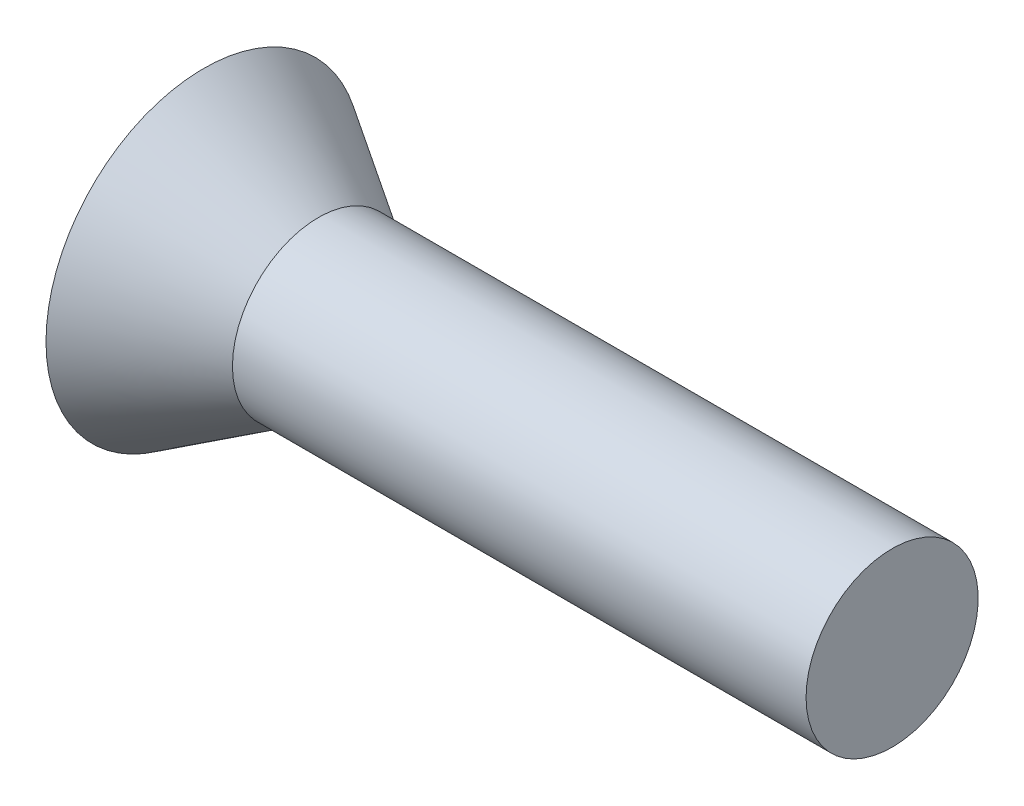
SolidWorks part; units mm, degrees
ref_plane "前视基准面" through (0, 0, 0) normal (0, 0, 1) x (1, 0, 0)
ref_plane "上视基准面" through (0, 0, 0) normal (0, 1, 0) x (1, 0, 0)
ref_plane "右视基准面" through (0, 0, 0) normal (1, 0, 0) x (0, 0, -1)
sketch "草图4" plane through (0, 0, 0) normal (0, 1, 0) x (1, 0, 0)
  line L0 (-2.1035, 0) -> (3.1765, 0) construction
  line L1 (0, 0) -> (0, 2.75)
  line L2 (0, 2.75) -> (2, 1.5)
  line L3 (2, 1.5) -> (12, 1.5)
  line L4 (12, 1.5) -> (12, 0)
  line L5 (12, 0) -> (0, 0)
  dimension "D1" = 2
  dimension "D2" = 2.75
  dimension "D3" = 1.5
  dimension "D4" = 10
revolve "旋转1" add sketch "草图4" angle 360 about L0
sketch "草图5" plane through (0, 0, 0) normal (-1, 0, 0) x (0, 0, 1)
  line L0 (-0.25, 0.25) -> (-1.25, 0.25)
  line L1 (1.25, -0.25) -> (0.25, -0.25)
  line L2 (1.25, -0.25) -> (1.25, 0.25)
  line L3 (1.25, 0.25) -> (0.25, 0.25)
  line L4 (-1.25, -0.25) -> (-1.25, 0.25)
  line L7 (0.25, -1.25) -> (-0.25, -1.25)
  line L8 (0.25, -1.25) -> (0.25, -0.25)
  line L9 (0.25, 1.25) -> (-0.25, 1.25)
  line L10 (-0.25, -1.25) -> (-0.25, -0.25)
  line L13 (-0.25, 0.25) -> (-0.25, 1.25)
  line L15 (0.25, 0.25) -> (0.25, 1.25)
  line L16 (-0.25, -0.25) -> (-1.25, -0.25)
  point P0 (0, 0)
  point P6 (0, 0)
  dimension "D1" = 0.5
  dimension "D2" = 0.5
  dimension "D3" = 2.5
  dimension "D4" = 2.5
extrude "切除-拉伸1" cut sketch "草图5" against normal blind 1
